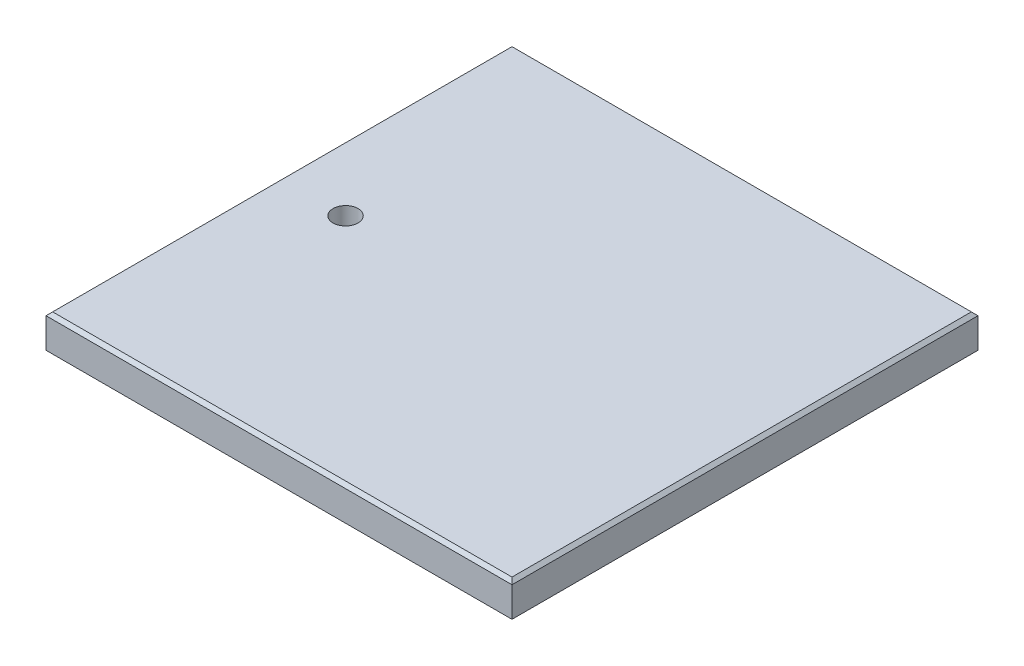
SolidWorks part; units mm, degrees
material "Acrylic (Medium-high impact)"
ref_plane "Front Plane" through (0, 0, 0) normal (0, 0, 1) x (1, 0, 0)
ref_plane "Top Plane" through (0, 0, 0) normal (0, 1, 0) x (1, 0, 0)
ref_plane "Right Plane" through (0, 0, 0) normal (1, 0, 0) x (0, 0, -1)
sketch "Sketch1" plane through (0, 0, 0) normal (0, 1, 0) x (1, 0, 0)
  line L1 (-44.45, 44.45) -> (44.45, 44.45)
  line L2 (-44.45, 44.45) -> (-44.45, -44.45)
  line L3 (-44.45, -44.45) -> (44.45, -44.45)
  line L4 (44.45, 44.45) -> (44.45, -44.45)
  line L5 (-44.45, 44.45) -> (44.45, -44.45) construction
  line L6 (-44.45, -44.45) -> (44.45, 44.45) construction
  point P0 (0, 0)
  dimension "D1" = 88.9
  dimension "D2" = 88.9
extrude "Boss-Extrude1" add sketch "Sketch1" along normal blind 12.7
sketch "Sketch2" plane through (0, 0, 0) normal (0, 1, 0) x (1, 0, 0)
  line L1 (-38.1, 38.1) -> (38.1, 38.1)
  line L2 (-38.1, 38.1) -> (-38.1, -38.1)
  line L3 (-38.1, -38.1) -> (38.1, -38.1)
  line L4 (38.1, 38.1) -> (38.1, -38.1)
  line L5 (-38.1, 38.1) -> (38.1, -38.1) construction
  line L6 (-38.1, -38.1) -> (38.1, 38.1) construction
  point P0 (0, 0)
  dimension "D1" = 76.2
  dimension "D2" = 76.2
extrude "Cut-Extrude3" cut sketch "Sketch2" along normal blind 6.35 flip side to cut
sketch "Sketch3" plane through (0, 12.7, 0) normal (0, 1, 0) x (1, 0, 0)
  line L1 (-31.75, 0) -> (0, 0) construction
  circle A2 centre (-31.75, 0) radius 2.3876
  dimension "D2" = 4.7752
  dimension "D1" = 31.75
extrude "Cut-Extrude4" cut sketch "Sketch3" against normal through all
chamfer "Chamfer1" distance 0.635 angle 45 4 edges at (44.45, 12.7, 0) (0, 12.7, 44.45) (-44.45, 12.7, 0) (0, 12.7, -44.45)
sketch "Sketch4" plane through (0, 0, 0) normal (0, -1, 0) x (1, 0, 0)
  line L0 (-31.75, 15.875) -> (-31.75, -15.875) construction
  circle A0 centre (-31.75, 15.875) radius 3.175
  circle A1 centre (-31.75, -15.875) radius 3.175
  point P4 (-31.75, 0)
  dimension "D2" = 6.35
  dimension "D1" = 31.75
extrude "Cut-Extrude5" cut sketch "Sketch4" against normal blind 7.62
